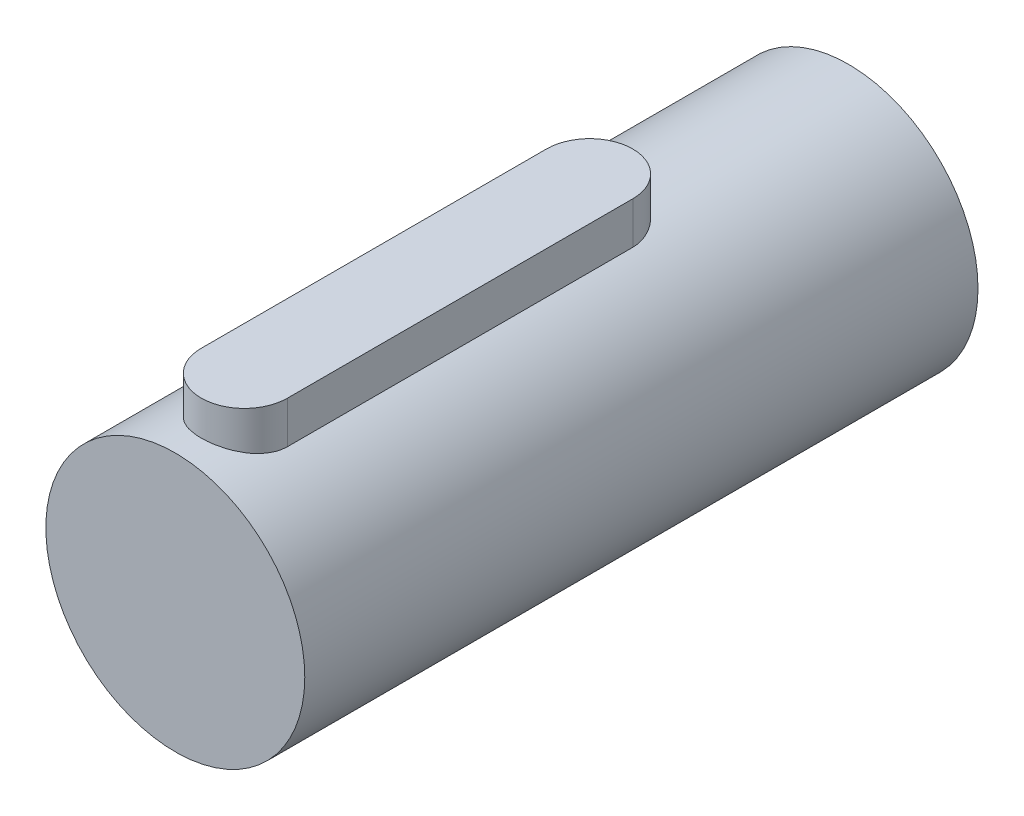
SolidWorks part; units mm, degrees
material "AISI 1045 Steel, cold drawn"
ref_plane "Frontal Plane" through (0, 0, 0) normal (0, 0, 1) x (1, 0, 0)
ref_plane "Horizontal Plane" through (0, 0, 0) normal (0, 1, 0) x (1, 0, 0)
ref_plane "Profile Plane" through (0, 0, 0) normal (1, 0, 0) x (0, 0, -1)
sketch "Sketch1" plane through (0, 0, 0) normal (0, 0, 1) x (1, 0, 0)
  circle A0 centre (0, 0) radius 7.5
  dimension "D1" = 15
extrude "Boss-Extrude1" add sketch "Sketch1" against normal blind 39
ref_plane "Plane1" through (0, 9.5, 0) normal (0, 1, 0) x (1, 0, 0)
sketch "Sketch2" plane through (0, 9.5, 0) normal (0, 1, 0) x (1, 0, 0)
  line L0 (0, 24) -> (0, 4) construction
  line L1 (2.5, 24) -> (2.5, 4)
  line L2 (-2.5, 24) -> (-2.5, 4)
  line L5 (-7.5, 0) -> (7.5, 0) construction
  arc A0 (2.5, 24) -> (-2.5, 24) centre (0, 24) ccw
  arc A1 (-2.5, 4) -> (2.5, 4) centre (0, 4) ccw
  point P2 (0, 14)
  dimension "D2" = 20
  dimension "D1" = 5
  dimension "D3" = 4
extrude "Boss-Extrude2" add sketch "Sketch2" against normal blind 5 separate body
equation "\"PinDiameter\"= 0"
equation "\"WallThickness\"= 0.5cm"
equation "\"ActuatorL\"= 35cm"
equation "\"Box-X\"= 40cm"
equation "\"Box-Z\"= 20cm"
equation "\"Box-Y\"= 30cm"
equation "\"BottomPlateX\"= 3ft"
equation "\"ArmPlateX\"= 18in"
equation "\"Arm1X\"= 5cm"
equation "\"Arm1L\"= 60cm"
equation "\"Arm2GAP\"= 5cm"
equation "\"Arm2L\"= 60cm"
equation "\"Arm2H\"= 5cm"
equation "\"Arm2Extension\"= 5cm"
equation "\"Arm3GAP\"= 5cm"
equation "\"Arm3L\"= 60cm"
equation "\"Arm3H\"= 5cm"
equation "\"Pin1-2L\"= \"Arm2GAP\" + (2 * \"WallThickness\")"
equation "\"Pin2-3L\"= \"Arm3GAP\" + (4 * \"WallThickness\")"
equation "\"DCMotor2L\"= 208mm"
equation "\"D1@Sketch1\"=\"DCMotor2ShaftD\""
equation "\"DCMotor2ShaftL\"= 39mm"
equation "\"D1@Boss-Extrude1\"=\"DCMotor2ShaftL\""
equation "\"RotaryUnionThickness\"= 1cm"
equation "\"ArmPlateThickness\"= .125in"
equation "\"DCMotor1D\"= 65mm"
equation "\"DCMotor1L\"= 215mm"
equation "\"DCMotor1ShaftL\"= 30mm"
equation "\"DCMotor2X\"= 68mm"
equation "\"DCMotor2D\"= 65mm"
equation "\"BenchDepth\"= 5cm"
equation "\"BenchH\"= 10cm"
equation "\"BenchL\"= 15cm"
equation "\"ActuatorPinD\"= 6.35mm"
equation "\"ActuatorPinL\"= 15cm"
equation "\"DCMotor2ShaftD\"= 15mm"
equation "\"PillowBlockW\"= 5cm"
equation "\"PillowBlockCenterH\"= \"DCMotor2X\"/2"
